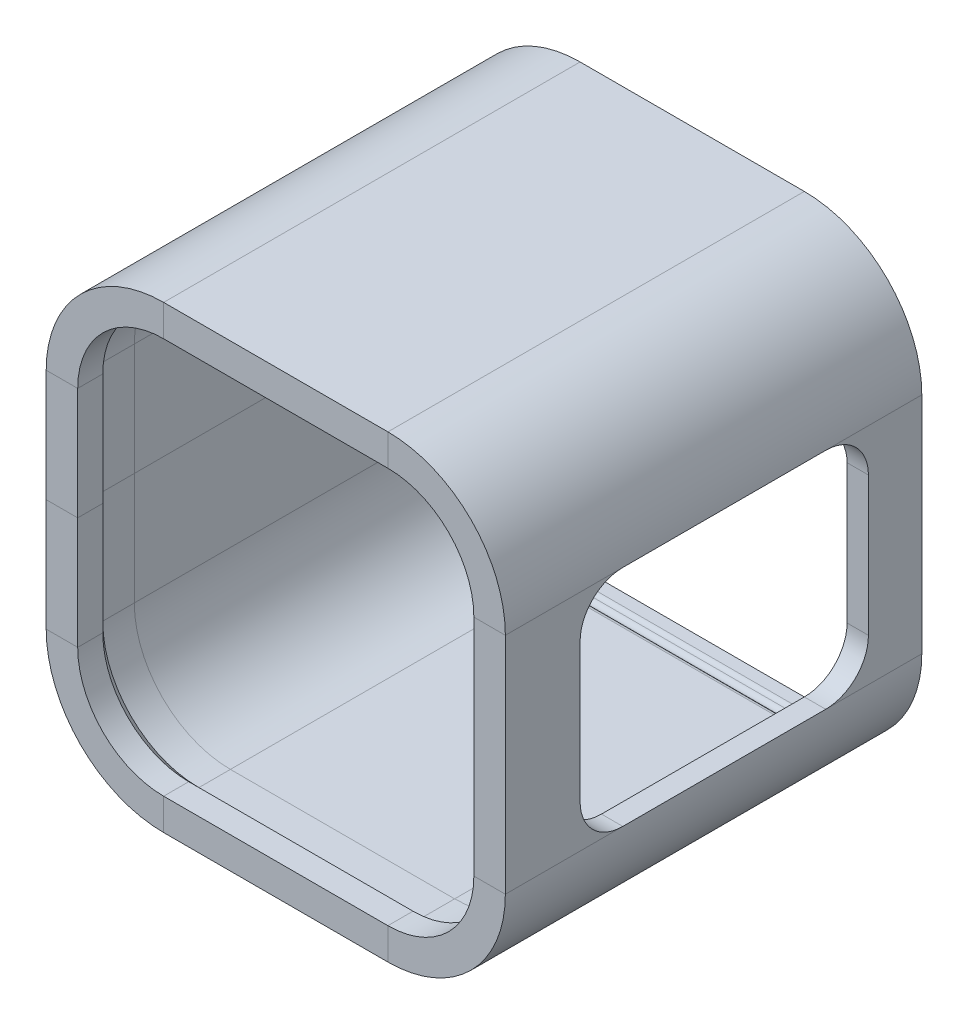
SolidWorks part; units mm, degrees
ref_plane "Front Plane" through (0, 0, 0) normal (0, 0, 1) x (1, 0, 0)
ref_plane "Top Plane" through (0, 0, 0) normal (0, 1, 0) x (1, 0, 0)
ref_plane "Right Plane" through (0, 0, 0) normal (1, 0, 0) x (0, 0, -1)
sketch "Sketch1" plane through (0, 0, 0) normal (0, 0, 1) x (1, 0, 0)
  line L1 (-10.5, -19.25) -> (10.5, -19.25)
  line L2 (-19.25, -10.5) -> (-19.25, 10.5)
  line L3 (-10.5, 19.25) -> (10.5, 19.25)
  line L4 (19.25, -10.5) -> (19.25, 10.5)
  line L5 (-19.25, -19.25) -> (19.25, 19.25) construction
  line L6 (-19.25, 19.25) -> (19.25, -19.25) construction
  arc A0 (-10.5, -19.25) -> (-19.25, -10.5) centre (-10.5, -10.5) cw
  arc A1 (10.5, -19.25) -> (19.25, -10.5) centre (10.5, -10.5) ccw
  arc A2 (10.5, 19.25) -> (19.25, 10.5) centre (10.5, 10.5) cw
  arc A3 (-19.25, 10.5) -> (-10.5, 19.25) centre (-10.5, 10.5) cw
  point P0 (0, 0)
  dimension "D3" = 8.75
  dimension "D1" = 38.5
  dimension "D2" = 38.5
sketch "Sketch4" plane through (0, 0, 0) normal (0, 1, 0) x (1, 0, 0)
  line L0 (-19.5, 0) -> (-19.5, -3)
  line L1 (-19.25, 0) -> (19.25, 0) construction
  line L2 (-19.25, 0) -> (19.25, 0) construction
  line L3 (-19.5, -3) -> (-19.45, -3)
  line L4 (-18.55, -3.9) -> (-18.55, -6.25)
  line L5 (-18.55, -6.25) -> (-21.5, -6.25)
  line L6 (-21.5, -6.25) -> (-21.5, 32.75)
  line L7 (-21.5, 32.75) -> (-19.5, 32.75)
  line L8 (-19.5, 32.75) -> (-19.5, 31.616)
  line L9 (-19.25, 0) -> (-10.5, 0) construction
  line L10 (-19.45, -3) -> (-18.55, -3.9)
  line L11 (-19.5, 29.884) -> (-19.5, 0)
  arc A0 (-19.75, 31.183) -> (-19.75, 30.317) centre (-19.5, 30.75) ccw
  arc A1 (-19.75, 31.183) -> (-19.5, 31.616) centre (-20, 31.616) ccw
  arc A2 (-19.75, 30.317) -> (-19.5, 29.884) centre (-20, 29.884) cw
  point P7 (-18.55, -3)
  point P23 (-19.5, 30.25)
  dimension "D8" = 1
  dimension "D9" = 0.5
  dimension "D1" = 0.95
  dimension "D2" = 2.95
  dimension "D3" = 3
  dimension "D4" = 39
  dimension "D5" = 3.25
  dimension "D6" = 21.5
  dimension "D7" = 2
sweep "Case" add profiles "Sketch4" path "Sketch1"
sketch "Sketch6" plane through (21.5, 0, 0) normal (1, 0, 0) x (0, 0, -1)
  line L0 (32.75, 10.5) -> (-6.25, 10.5) construction
  line L1 (23.75, 10.5) -> (4.75, 10.5)
  line L2 (27.75, 6.5) -> (27.75, -6.5)
  line L3 (23.75, -10.5) -> (4.75, -10.5)
  line L4 (0.75, 6.5) -> (0.75, -6.5)
  line L5 (32.75, -10.5) -> (-6.25, -10.5) construction
  line L6 (32.75, -10.5) -> (32.75, 10.5) construction
  line L7 (-6.25, -10.5) -> (-6.25, 10.5) construction
  arc A0 (23.75, 10.5) -> (27.75, 6.5) centre (23.75, 6.5) cw
  arc A1 (27.75, -6.5) -> (23.75, -10.5) centre (23.75, -6.5) cw
  arc A2 (4.75, -10.5) -> (0.75, -6.5) centre (4.75, -6.5) cw
  arc A3 (4.75, 10.5) -> (0.75, 6.5) centre (4.75, 6.5) ccw
  point P14 (27.75, 10.5)
  point P19 (0.75, -10.5)
  dimension "D3" = 4
  dimension "D1" = 5
  dimension "D2" = 7
extrude "Power Button Hole" cut sketch "Sketch6" against normal blind 2
sketch "Sketch7" plane through (-21.5, 0, 0) normal (-1, 0, 0) x (0, 0, 1)
  line L0 (-32.75, 10.5) -> (6.25, 10.5) construction
  line L1 (-4.25, 10.5) -> (-22.25, 10.5)
  line L2 (-4.25, 10.5) -> (-4.25, -10.5)
  line L3 (-4.25, -10.5) -> (-22.25, -10.5)
  line L4 (-22.25, 10.5) -> (-22.25, -10.5)
  line L5 (-32.75, -10.5) -> (6.25, -10.5) construction
  line L6 (-32.75, 10.5) -> (-32.75, 0) construction
  point P8 (-13.25, 10.5)
  dimension "D1" = 18
  dimension "D2" = 19.5
ref_plane "Plane1" through (0, 0, -42.75) normal (0, 0, -1) x (-1, 0, 0)
ref_plane "Plane2" through (0, 0, 16.25) normal (0, 0, 1) x (1, 0, 0)
